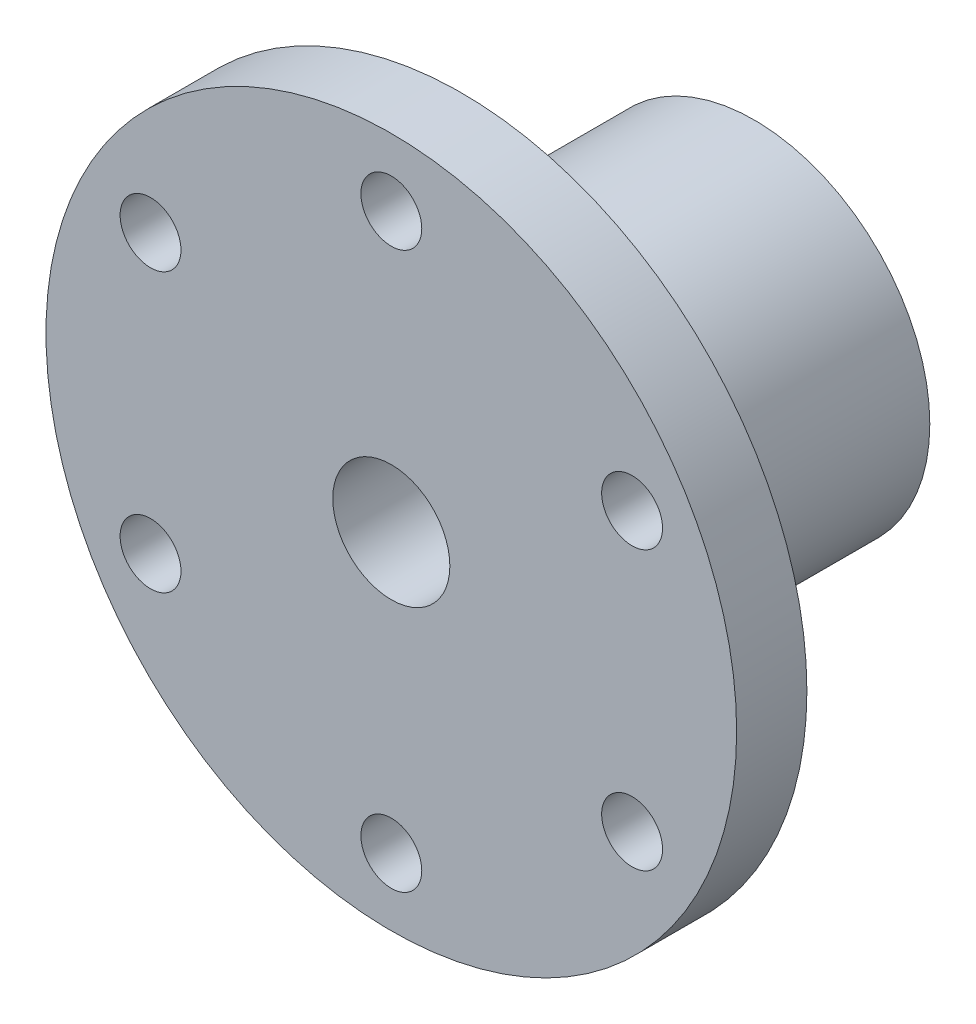
SolidWorks part; units mm, degrees
ref_plane "Front Plane" through (0, 0, 0) normal (0, 0, 1) x (1, 0, 0)
ref_plane "Top Plane" through (0, 0, 0) normal (0, 1, 0) x (1, 0, 0)
ref_plane "Right Plane" through (0, 0, 0) normal (1, 0, 0) x (0, 0, -1)
sketch "Sketch1" plane through (0, 0, 0) normal (0, 0, 1) x (1, 0, 0)
  line L0 (0, 0) -> (0, 34601.9221) construction
  line L1 (0, 0) -> (-34601.9221, 0) construction
  circle A0 centre (0, 0) radius 29.5
  circle A1 centre (0, 0) radius 23.75 construction
  circle A2 centre (0, 23.75) radius 2.6
  circle A3 centre (20.5681, 11.875) radius 2.6
  circle A4 centre (20.5681, -11.875) radius 2.6
  circle A5 centre (0, -23.75) radius 2.6
  circle A6 centre (-20.5681, -11.875) radius 2.6
  circle A7 centre (-20.5681, 11.875) radius 2.6
  point P23 (0, 0)
  dimension "D1" = 59
  dimension "D2" = 47.5
  dimension "D3" = 5.2
  dimension "D4" = 6
extrude "Boss-Extrude1" add sketch "Sketch1" along normal blind 6
sketch "Sketch2" plane through (0, 0, 0) normal (1, 0, 0) x (0, 0, -1)
  line L0 (0, 0) -> (50000, 0) construction
  line L1 (0, 0) -> (25, 0)
  line L4 (25, 0) -> (25, 15)
  line L5 (25, 15) -> (0, 15)
  line L6 (0, 15) -> (0, 0)
  line L7 (0, 0) -> (0, 50000) construction
  dimension "D1" = 25
  dimension "D2" = 15
revolve "Revolve1" add sketch "Sketch2" angle 360 about L1
fillet "Fillet1" radius 1 1 edges at (15, 0, 0)
sketch "Sketch3" plane through (0, 0, -25) normal (0, 0, -1) x (-1, 0, 0)
  circle A0 centre (0, 0) radius 5
  dimension "D1" = 10
extrude "Cut-Extrude1" cut sketch "Sketch3" against normal up to surface (31 mm away) up to face at (-17.9681, -11.875, 6)
